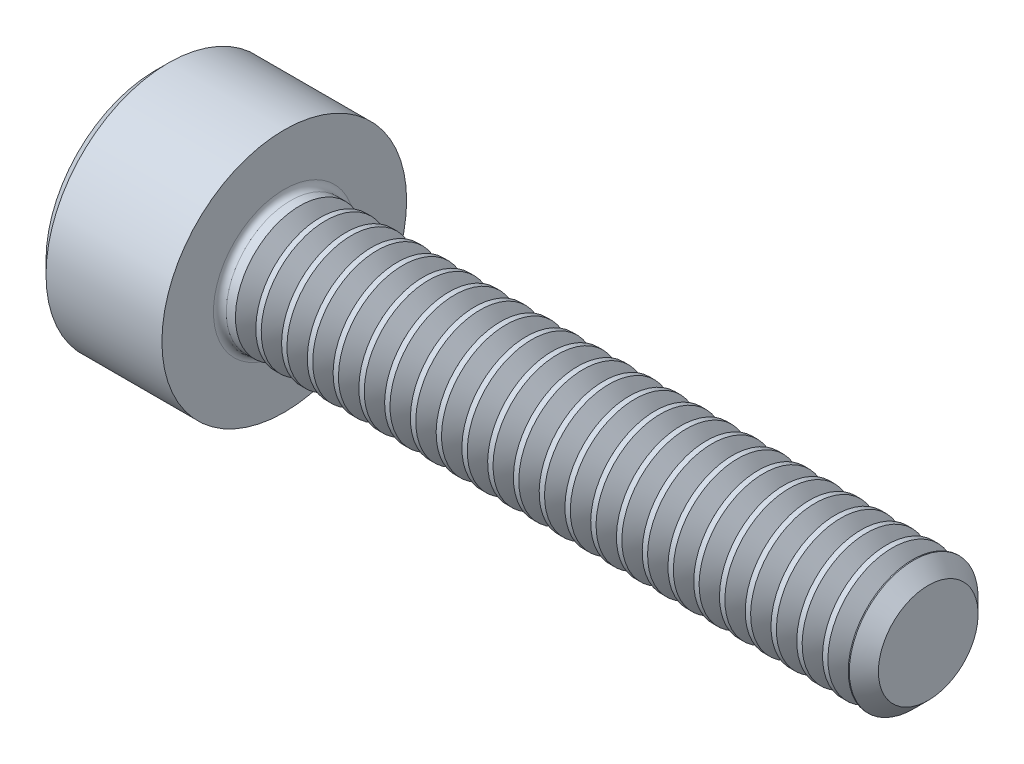
SolidWorks part; units mm, degrees
revolve "Base-Revolve" add sketch "BodySke"
sketch "BodySke" plane through (0, 0, 0) normal (0, 0, 1) x (1, 0, 0)
  line L0 (0, 0) -> (0, 1.7)
  line L1 (0.2, 1.9) -> (2, 1.9)
  line L2 (2, 1.9) -> (2, 1)
  line L3 (2, 1) -> (11.774, 1)
  line L4 (12, 0.774) -> (12, 0)
  line L5 (12, 0) -> (0, 0)
  line L6 (-31.75, 0) -> (127, 0) construction
  line L7 (0, 1.7) -> (0.2, 1.9)
  line L8 (12, 0.774) -> (11.774, 1)
  line L9 (0, -1.7) -> (0.2, -1.9) construction
  line L10 (12, -0.774) -> (11.774, -1) construction
  line L11 (2.4, 9.525) -> (2.4, 3.175) construction
  line L12 (2, 9.525) -> (2, 3.175) construction
  line L13 (-38, 9.525) -> (-38, 3.175) construction
  dimension "Diameter" = 2
  dimension "Head_ht" = 2
  dimension "Length" = 10
  dimension "Body_ch_ang" = 45
  dimension "Head_dia" = 3.8
  dimension "Head_ch_ang" = 45
  dimension "Minor_dia" = 1.548
  dimension "Advance" = 0.4
  dimension "Thread_nom" = 10
  dimension "Thread_length" = 50
  dimension "Head_ch_ht" = 0.2
cosmetic thread "ThreadCosmetic" [suppressed]
fillet "Fillet1" radius 0.1 1 edges at (2, 0, 1)
ref_plane "Plane1" through (0, 0, 0) normal (0, 0, 1) x (1, 0, 0)
ref_plane "Plane2" through (0, 0, 0) normal (0, 1, 0) x (1, 0, 0)
ref_plane "Plane3" through (0, 0, 0) normal (1, 0, 0) x (0, 0, -1)
sketch "Sketch2" plane through (0, 0, 0) normal (0, 0, 1) x (1, 0, 0)
  line L0 (0, 0.7725) -> (1, 0.7725)
  line L1 (1, 0.7725) -> (1.446, 0)
  line L2 (-31.75, 0) -> (127, 0) construction
  line L3 (1.446, 0) -> (0, 0)
  line L4 (0, 0) -> (0, 0.7725)
  line L5 (0, 1.7) -> (0, -1.7) construction
  line L6 (0, 0) -> (47.625, 0) construction
  line L7 (2, -1.9) -> (2, 1.9) construction
  dimension "D1" = 0.7725
  dimension "D2" = 60
revolve "Hex-PreBroach" cut sketch "Sketch2" angle 360 about L6
sketch "Sketch3" plane through (0, 0, 0) normal (-1, 0, 0) x (0, 0.5, 0.866)
  line L0 (0.446, 0.7725) -> (-0.446, 0.7725)
  line L1 (-0.446, 0.7725) -> (-0.892, 0)
  line L2 (0.446, 0.7725) -> (0.892, 0)
  line L3 (0.446, -0.7725) -> (0.892, 0)
  line L4 (0.446, -0.7725) -> (-0.446, -0.7725)
  line L5 (-0.446, -0.7725) -> (-0.892, 0)
  dimension "D1" = 0.7725
  dimension "D2" = 0.7725
  dimension "Hex_size" = 1.545
extrude "Hex" cut sketch "Sketch3" against normal blind 1
sketch "Sketch4" plane through (0, 0, 0) normal (-1, 0, 0) x (0, 0, 1)
  line L0 (0, 0) -> (0.9398, 0)
  line L1 (0, 0) -> (6.1484, 3.5498) construction
  line L2 (0, 0) -> (0.4699, 0.8139)
  line L3 (0.7832, 0.2175) -> (0.8962, 0.2828)
  line L4 (0.58, 0.5695) -> (0.693, 0.6348)
  arc A0 (0.7832, 0.2175) -> (0.58, 0.5695) centre (0, 0) ccw
  arc A1 (0.9398, 0) -> (0.8962, 0.2828) centre (0, 0) ccw
  arc A2 (0.4699, 0.8139) -> (0.693, 0.6348) centre (0, 0) cw
  dimension "D1" = 30
  dimension "D2" = 60
  dimension "Spline_p_dim" = 0.4064
  dimension "D3" = 0.2032
extrude "Spline" [suppressed] cut sketch "Sketch4" against normal blind 1
pattern_circular "CirPattern1" [suppressed] count 6 every 60
sketch "Sketch5" plane through (0, 0, 0) normal (0, 0, 1) x (1, 0, 0)
  line L0 (-31.75, 0) -> (127, 0) construction
  line L2 (0, 1.7) -> (0, -1.7) construction
  circle A0 centre (0.1, 0) radius 0.005
  dimension "Drilled_hole_dia" = 0.01
  dimension "Drilled_hole_loc" = 0.1
extrude "Hole" [suppressed] cut sketch "Sketch5" against normal through all and the other way through all
pattern_circular "Drilled-4" [suppressed] count 2 every 60
pattern_circular "Drilled-6" [suppressed] count 3 every 60
sketch "ThdSchSke" plane through (0, 0, 0) normal (0, 0, 1) x (1, 0, 0)
  line L0 (2.4, -0.774) -> (2.2418, -1)
  line L1 (2.4, -0.774) -> (2.5582, -1)
  line L2 (2.5582, -1) -> (2.5582, -1.25)
  line L3 (-3.175, 0) -> (5.1513, 0) construction
  line L5 (2.5582, -1.25) -> (2.2418, -1.25)
  line L6 (2.2418, -1.25) -> (2.2418, -1)
  line L7 (0, 1.7) -> (0, -1.7) construction
  dimension "Thread_minor" = 1.548
  dimension "Diameter" = 2
  dimension "Start" = 2.4
revolve "ThreadSchematic" cut sketch "ThdSchSke" angle 360 about L3
pattern_linear "ThdSchPat" count 24 spacing 0.4 along (1, 0, 0) of "ThreadSchematic"
equation "\"D2@Sketch3\" = \"Hex_size@Sketch3\" / 2"
equation "\"D1@Sketch3\" = \"Hex_size@Sketch3\" / 2"
equation "\"D1@Sketch2\" = \"Hex_size@Sketch3\" / 2"
equation "\"D3@Sketch4\" = \"Spline_p_dim@Sketch4\" / 2"
equation "\"Thread_minor@ThreadCosmetic\"  =  \"Minor_dia@BodySke\""
equation "\"D2@CirPattern1\" = 360 / \"Num_teeth@CirPattern1\""
equation "\"Wall_thickness@Sketch2\" = \"Head_ht@BodySke\" - \"Key_eng@Hex\""
equation "\"Thread_length@ThreadCosmetic\" = ((sgn( (\"Length@BodySke\" - \"Advance@BodySke\" ) - \"Thread_nom@BodySke\" )-1)*( (\"Length@BodySke\" - \"Advance@BodySke\" ) - \"Thread_nom@BodySke\" ))/-2+ \"Thread_nom@BodySke\""
equation "\"Thread_minor@ThdSchSke\" = \"Minor_dia@BodySke\""
equation "\"Diameter@ThdSchSke\" = \"Diameter@BodySke\""
equation "\"Overcut@ThdSchSke\" = \"Diameter@BodySke\" * 1.25"
equation "\"Start@ThdSchSke\" = \"Head_ht@BodySke\" + \"Length@BodySke\" - \"Thread_length@ThreadCosmetic\"  '---Non-countersunk---"
equation "\"Num_threads@ThdSchPat\" = int( \"Thread_length@ThreadCosmetic\" / \"Advance@BodySke\" + 0.999 )  + 1"
equation "\"Advance@ThdSchPat\" = \"Thread_length@ThreadCosmetic\" /  (\"Num_threads@ThdSchPat\" - 1) 'relax it"
equation "\"Num_threads@ThdSchPat\" = \"Num_threads@ThdSchPat\" - sgn( \"Num_threads@ThdSchPat\" - 1) '---chamfered tips only---"
